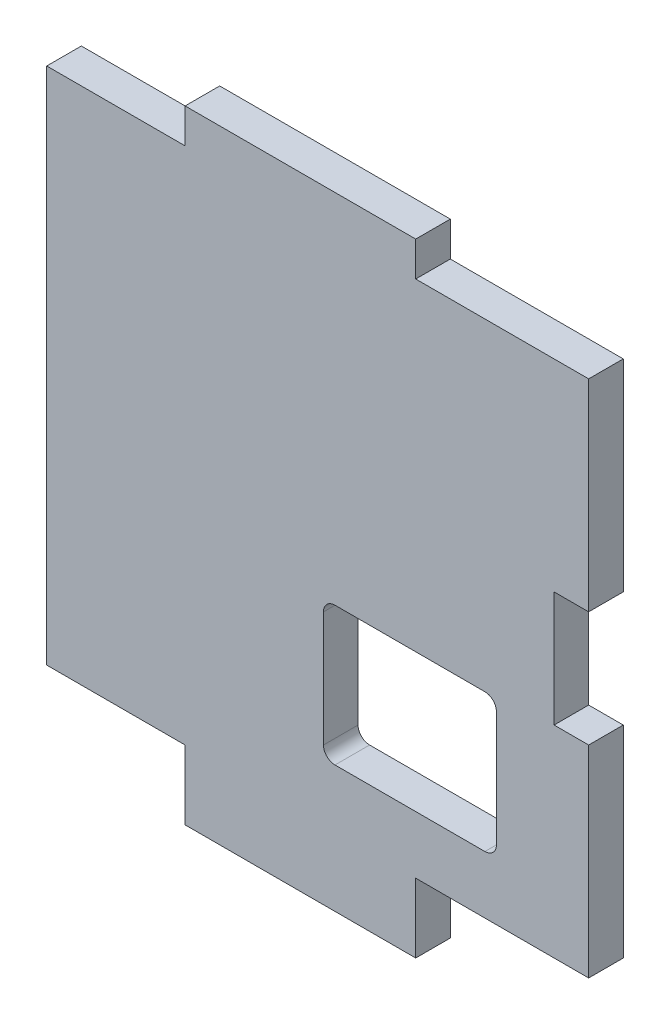
SolidWorks part; units mm, degrees
ref_plane "Front Plane" through (0, 0, 0) normal (0, 0, 1) x (1, 0, 0)
ref_plane "Top Plane" through (0, 0, 0) normal (0, 1, 0) x (1, 0, 0)
ref_plane "Right Plane" through (0, 0, 0) normal (1, 0, 0) x (0, 0, -1)
sketch "Sketch1" plane through (0, 0, 0) normal (0, 0, 1) x (1, 0, 0)
  line L0 (0, 0) -> (0, 45)
  line L1 (0, 45) -> (12, 45)
  line L2 (12, 45) -> (12, 48)
  line L3 (12, 48) -> (32, 48)
  line L4 (32, 48) -> (32, 45)
  line L5 (32, 45) -> (47, 45)
  line L6 (47, 45) -> (47, 27.5)
  line L7 (47, 27.5) -> (44, 27.5)
  line L8 (44, 27.5) -> (44, 17.5)
  line L9 (44, 17.5) -> (47, 17.5)
  line L10 (47, 17.5) -> (47, 0)
  line L11 (47, 0) -> (32, 0)
  line L12 (32, 0) -> (32, -6)
  line L13 (32, -6) -> (12, -6)
  line L14 (12, -6) -> (12, 0)
  line L15 (12, 0) -> (0, 0)
  dimension "D1" = 6
  dimension "D2" = 20
  dimension "D3" = 45
  dimension "D4" = 10
  dimension "D5" = 3
  dimension "D6" = 47
  dimension "D7" = 15
extrude "Boss-Extrude1" add sketch "Sketch1" along normal blind 3
sketch "Sketch2" plane through (0, 0, 3) normal (0, 0, 1) x (1, 0, 0)
  line L0 (44, 17.5) -> (44, 27.5) construction
  line L1 (24, 17) -> (39, 17)
  line L2 (24, 17) -> (24, 5)
  line L3 (24, 5) -> (39, 5)
  line L4 (39, 17) -> (39, 5)
  line L5 (32, 0) -> (47, 0) construction
  dimension "D1" = 15
  dimension "D2" = 12
  dimension "D3" = 5
  dimension "D4" = 5
extrude "Cut-Extrude1" cut sketch "Sketch2" against normal through all
fillet "Fillet1" radius 1 4 edges at (39, 5, 1.5) (39, 17, 1.5) (24, 17, 1.5) (24, 5, 1.5)
